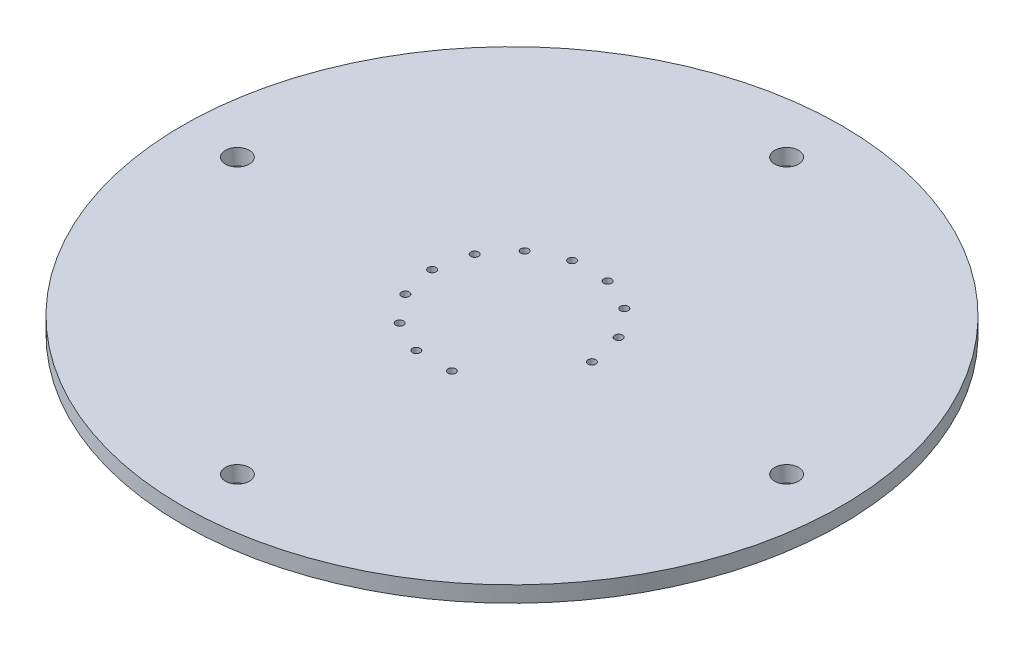
SolidWorks part; units mm, degrees
ref_plane "Front Plane" through (0, 0, 0) normal (0, 0, 1) x (1, 0, 0)
ref_plane "Top Plane" through (0, 0, 0) normal (0, 1, 0) x (1, 0, 0)
ref_plane "Right Plane" through (0, 0, 0) normal (1, 0, 0) x (0, 0, -1)
sketch "Sketch1" plane through (0, 0, 0) normal (0, 1, 0) x (1, 0, 0)
  circle A0 centre (0, 0) radius 33
extrude "Boss-Extrude1" add sketch "Sketch1" along normal blind 1.6
sketch "Sketch2" plane through (0, 1.6, 0) normal (0, 1, 0) x (1, 0, 0)
  line L0 (0, 0) -> (27.5, 0) construction
  line L1 (27.5, 0) -> (-27.5, 0) construction
  circle A0 centre (0, 27.5) radius 1.2
  circle A1 centre (27.5, 0) radius 1.2
  circle A2 centre (0, -27.5) radius 1.2
  circle A6 centre (-27.5, 0) radius 1.2
  dimension "D1" = 4
  dimension "D2" = 2.4
  dimension "D3" = 2.4
  dimension "D4" = 2.4
extrude "Cut-Extrude1" cut sketch "Sketch2" against normal blind 3
sketch "Sketch3" plane through (0, 1.6, 0) normal (0, 1, 0) x (1, 0, 0)
  circle A0 centre (0, 0) radius 3.75
  dimension "D1" = 7.5
extrude "Cut-Extrude2" cut sketch "Sketch3" against normal blind 3
sketch "Sketch4" plane through (0, 1.6, 0) normal (0, 1, 0) x (1, 0, 0)
  circle A0 centre (-5.4058, 2.6033) radius 0.35
  circle A1 centre (-6, 0) radius 0.35
  circle A2 centre (-3.7409, 4.691) radius 0.35
  circle A3 centre (-1.3351, 5.8496) radius 0.35
  circle A4 centre (1.3351, 5.8496) radius 0.35
  circle A5 centre (3.7409, 4.691) radius 0.35
  circle A6 centre (5.4058, 2.6033) radius 0.35
  circle A7 centre (6, 0) radius 0.35
  circle A8 centre (5.4058, -2.6033) radius 0.35
  circle A9 centre (3.7409, -4.691) radius 0.35
  circle A10 centre (1.3351, -5.8496) radius 0.35
  circle A11 centre (-1.3351, -5.8496) radius 0.35
  circle A12 centre (-3.7409, -4.691) radius 0.35
  circle A13 centre (-5.4058, -2.6033) radius 0.35
  dimension "D1" = 14
sketch "Sketch5" plane through (0, 1.6, 0) normal (0, 1, 0) x (1, 0, 0)
  line L0 (0, 0) -> (-1.3351, 5.8496) construction
  line L1 (-1.3351, 5.8496) -> (-1.7802, 7.7994) construction
  circle A0 centre (-1.7802, 7.7994) radius 0.39
  circle A1 centre (1.7802, 7.7994) radius 0.39
  circle A2 centre (4.9879, 6.2547) radius 0.39
  circle A3 centre (7.2078, 3.4711) radius 0.39
  circle A4 centre (8, 0) radius 0.39
  circle A7 centre (1.7802, -7.7994) radius 0.39
  circle A8 centre (-1.7802, -7.7994) radius 0.39
  circle A9 centre (-4.9879, -6.2547) radius 0.39
  circle A10 centre (-7.2078, -3.4711) radius 0.39
  circle A11 centre (-8, 0) radius 0.39
  circle A12 centre (-7.2078, 3.4711) radius 0.39
  circle A13 centre (-4.9879, 6.2547) radius 0.39
  circle A28 centre (4.9879, -6.2547) radius 0.39 [skipped]
  circle A29 centre (7.2078, -3.4711) radius 0.39 [skipped]
  dimension "D1" = 14
extrude "Cut-Extrude4" cut sketch "Sketch5" against normal blind 10
sketch "Sketch6" plane through (0, 1.6, 0) normal (0, 1, 0) x (1, 0, 0)
  circle A0 centre (0, 0) radius 3.75
extrude "Boss-Extrude2" add sketch "Sketch6" against normal blind 1.7
sketch "Sketch7" plane through (0, 1.6, 0) normal (0, 1, 0) x (1, 0, 0)
